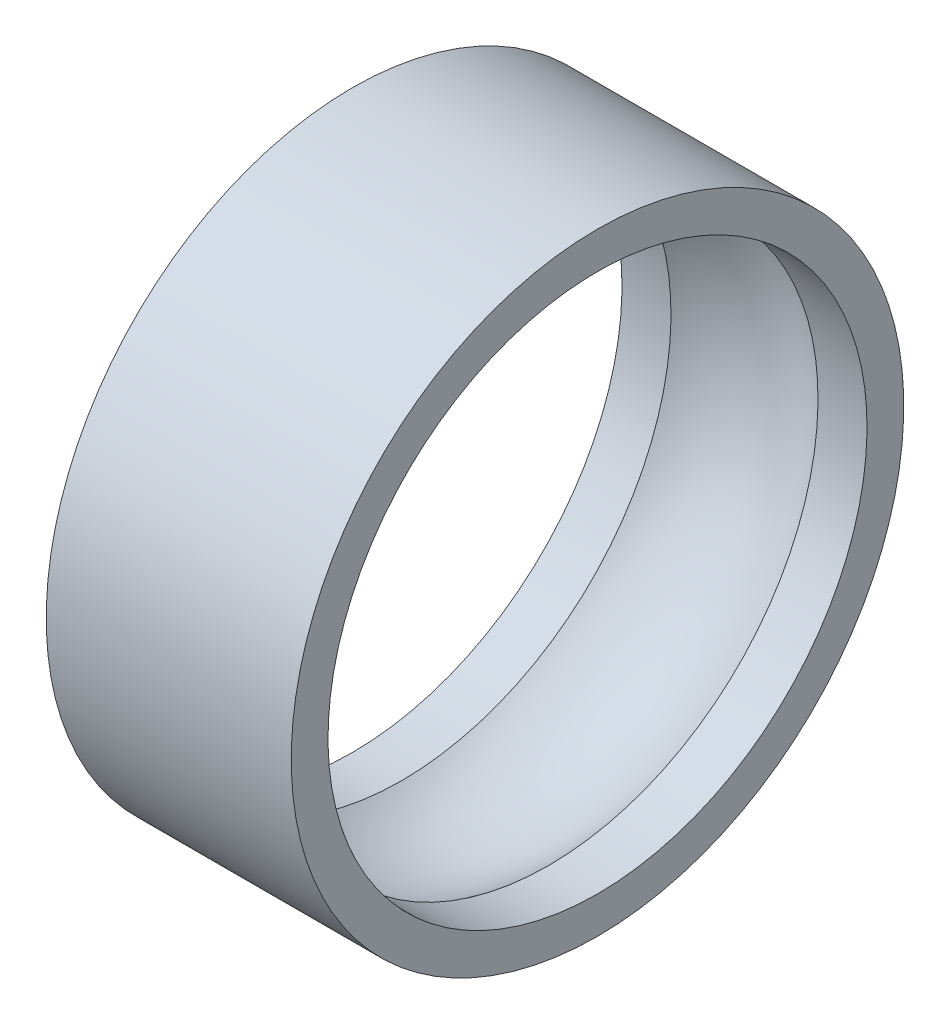
SolidWorks part; units mm, degrees
ref_plane "Front Plane" through (0, 0, 0) normal (0, 0, 1) x (1, 0, 0)
ref_plane "Top Plane" through (0, 0, 0) normal (0, 1, 0) x (1, 0, 0)
ref_plane "Right Plane" through (0, 0, 0) normal (1, 0, 0) x (0, 0, -1)
sketch "Sketch2" plane through (0, 0, 0) normal (0, 0, 1) x (1, 0, 0)
  line L0 (-10, 0) -> (39.0063, 0) construction
  line L1 (0, 23.5) -> (0, 0) construction
  line L2 (10, 25) -> (-10, 25)
  line L3 (10, 25) -> (10, 22)
  line L4 (10, 22) -> (6, 22)
  line L5 (-10, 25) -> (-10, 22)
  line L6 (10, 25) -> (-10, 22) construction
  line L7 (10, 22) -> (-10, 25) construction
  line L8 (-6, 22) -> (-10, 22)
  arc A0 (-6, 22) -> (6, 22) centre (0, 14) cw
  point P3 (0, 23.5)
  dimension "D5" = 10
  dimension "D1" = 25
  dimension "D2" = 20
  dimension "D3" = 22
  dimension "D4" = 8
revolve "Revolve1" add sketch "Sketch2" angle 360 about L0
